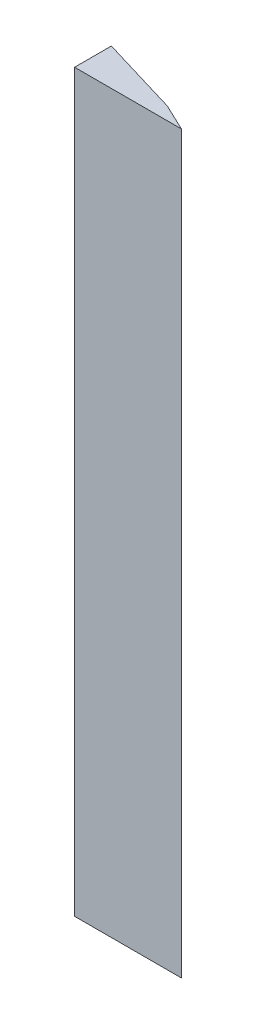
SolidWorks part; units mm, degrees
ref_plane "Front Plane" through (0, 0, 0) normal (0, 0, 1) x (1, 0, 0)
ref_plane "Top Plane" through (0, 0, 0) normal (0, 1, 0) x (1, 0, 0)
ref_plane "Right Plane" through (0, 0, 0) normal (1, 0, 0) x (0, 0, -1)
sketch "Sketch2" plane through (0, 0, 0) normal (0, 1, 0) x (1, 0, 0)
  line L0 (0, 0) -> (0, 7.5)
  line L1 (0, 7.5) -> (25, 0)
  line L2 (25, 0) -> (0, 0)
extrude "Boss-Extrude1" add sketch "Sketch2" along normal blind 150
sketch "Sketch3" plane through (0, 150, 0) normal (0, 1, 0) x (1, 0, 0)
  line L0 (16.3101, 2.607) -> (21.7892, 0)
  line L1 (25, 0) -> (0, 7.5) construction
  line L2 (0, 0) -> (25, 0) construction
  line L3 (21.7892, 0) -> (25, 0)
  line L4 (25, 0) -> (16.3101, 2.607)
extrude "Cut-Extrude1" cut sketch "Sketch3" against normal blind 150
